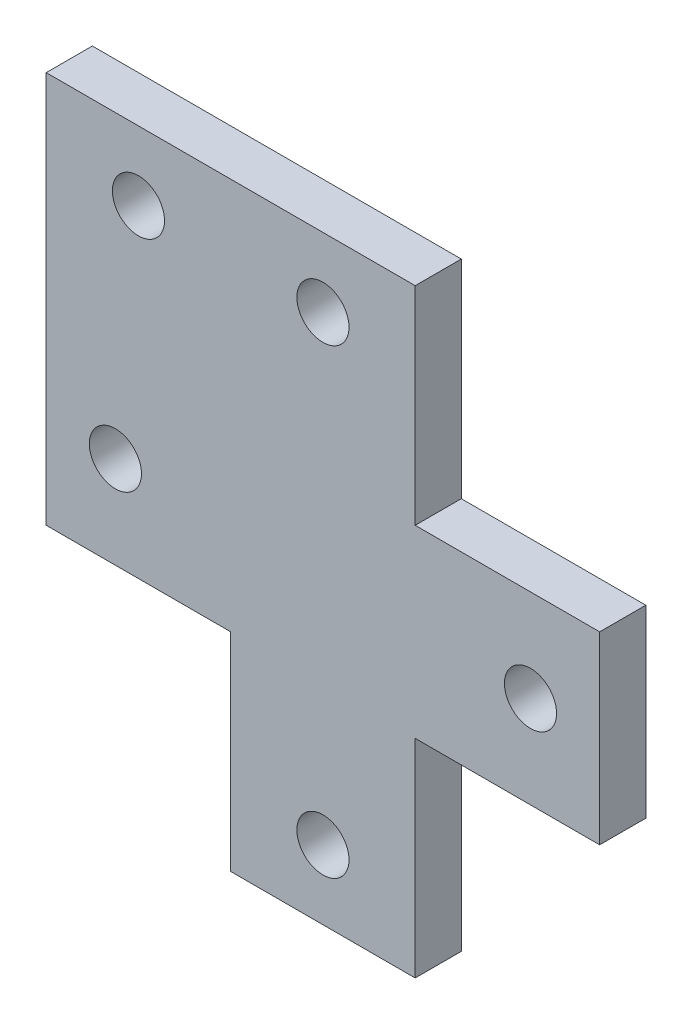
SolidWorks part; units mm, degrees
ref_plane "Front Plane" through (0, 0, 0) normal (0, 0, 1) x (1, 0, 0)
ref_plane "Top Plane" through (0, 0, 0) normal (0, 1, 0) x (1, 0, 0)
ref_plane "Right Plane" through (0, 0, 0) normal (1, 0, 0) x (0, 0, -1)
sketch "Sketch3" plane through (0, 0, 0) normal (0, 0, 1) x (1, 0, 0)
  line L0 (-5, -13) -> (13, -13) construction
  line L1 (0, 0) -> (8, 0)
  line L2 (0, 0) -> (0, -26)
  line L4 (8, 0) -> (8, -26)
  line L5 (-8, -9) -> (16, -9)
  line L6 (-8, -9) -> (-8, -17)
  line L7 (-8, -17) -> (16, -17)
  line L8 (16, -9) -> (16, -17)
  line L9 (4, -3) -> (4, -23) construction
  line L10 (0, -26) -> (8, -26)
  line L25 (0, 0) -> (-8, 0)
  line L26 (-8, 0) -> (-8, -9)
  circle A0 centre (-5, -13) radius 1
  circle A1 centre (13, -13) radius 1
  circle A2 centre (4, -3) radius 1
  circle A3 centre (4, -23) radius 1
  circle A10 centre (-4, -3) radius 1
  point P13 (4, 0)
  point P14 (4, -9)
  point P16 (16, -13)
  point P18 (4, -13)
  point P23 (0, 0)
  point P25 (0, 0)
  point P48 (4, -13)
  dimension "D6" = 2
  dimension "D1" = 18
  dimension "D2" = 8
  dimension "D3" = 8
  dimension "D4" = 9
  dimension "D7" = 9
  dimension "D5" = 3
  dimension "D8" = 26
  dimension "D10" = 20
  dimension "D9" = 4
  dimension "D11" = 3
extrude "Boss-Extrude1" add sketch "Sketch3" along normal blind 2
hole_wizard "#4-40 Tapped Hole1" positions "3DSketch1" profile "Sketch4" tap size "#4-40" standard "ANSI Inch" end condition through all
sketch3d "3DSketch1"
  line L0 (-5, -13, 2) -> (-5, -13, 0) construction
  line L1 (13, -13, 2) -> (13, -13, 0) construction
  circle A0 centre (-4, -3, 2) radius 1 construction
  point P0 (-5, -13, 2)
  point P4 (13, -13, 2)
  point P28 (4, -23, 2)
  point P30 (4, -3, 2)
  point P58 (-4, -3, 2)
  point P61 (0, 0, 0)
  point P64 (-4, -3, 3)
sketch "Sketch4" plane through (-5, -13, 2) normal (1, 0, 0) x (0, -1, 0)
  line L0 (0, 0) -> (0, 2)
  line L1 (0, 2) -> (1.1303, 2)
  line L2 (1.1303, 2) -> (1.1303, 0)
  line L5 (1.1303, 0) -> (0, 0)
  line L11 (0, -6.35) -> (0, 107.95) construction
  dimension "Thru Tap Drill Dia." = 2.2606
  dimension "Thru Tap Drill Depth" = 2
cosmetic thread "Hole Thread3" parameters "D2"=2.8448
cosmetic thread "Hole Thread4" parameters "D2"=2.8448
cosmetic thread "Hole Thread5" parameters "D2"=2.8448
cosmetic thread "Hole Thread6" parameters "D2"=2.8448
cosmetic thread "Hole Thread11" parameters "D2"=2.8448
equation "\"D7@Sketch3\"=\"D4@Sketch3\""
equation "\"D9@Sketch3\"=\"D3@Sketch3\"/2"
